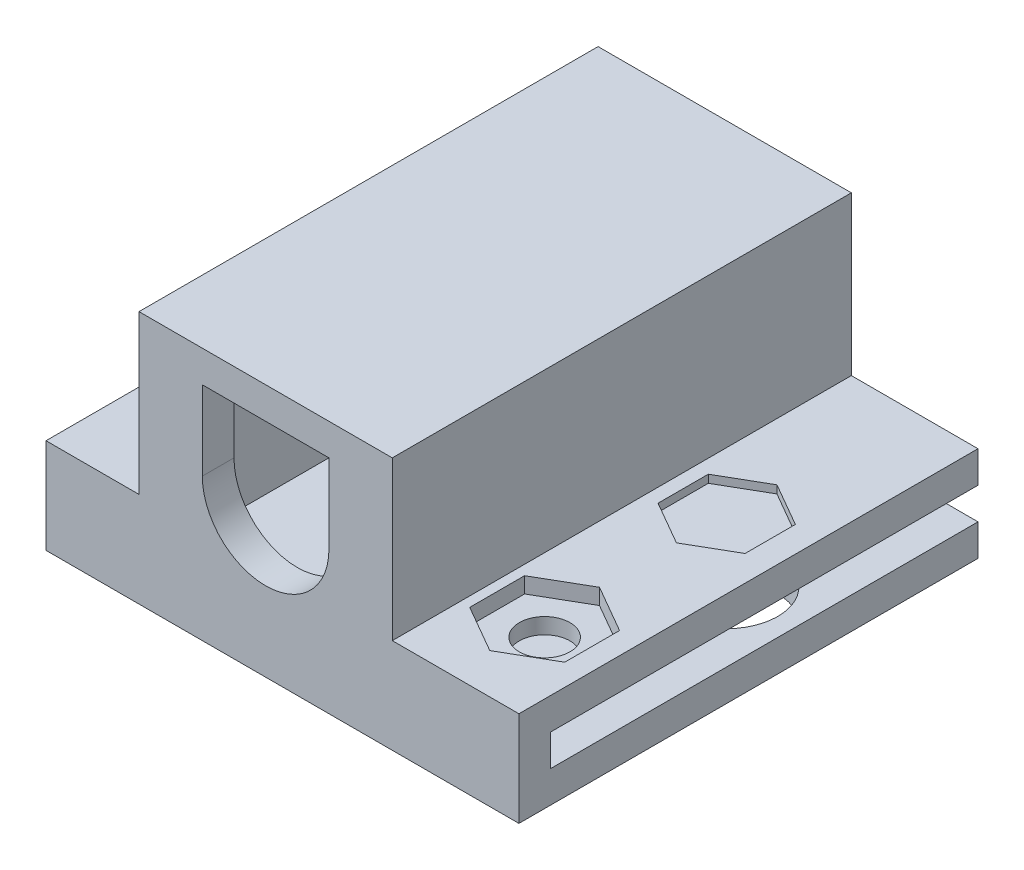
SolidWorks part; units mm, degrees
ref_plane "前视基准面" through (0, 0, 0) normal (0, 0, 1) x (1, 0, 0)
ref_plane "上视基准面" through (0, 0, 0) normal (0, 1, 0) x (1, 0, 0)
ref_plane "右视基准面" through (0, 0, 0) normal (1, 0, 0) x (0, 0, -1)
sketch "草图1" plane through (0, 0, 0) normal (0, 0, 1) x (1, 0, 0)
  line L1 (-13.875, -3) -> (-8, -3)
  line L2 (-13.875, -3) -> (-13.875, -9)
  line L3 (-13.875, -9) -> (16, -9)
  line L4 (5.5, 5) -> (-5.5, 5)
  line L5 (-6, 4.5) -> (-6, -4.5)
  line L6 (-5.5, -5) -> (5.5, -5)
  line L7 (6, -4.5) -> (6, 4.5)
  line L8 (5.5, 5) -> (-5.5, 5)
  line L9 (-6, 4.5) -> (-6, -4.5)
  line L10 (-5.5, -5) -> (5.5, -5)
  line L11 (6, -4.5) -> (6, 4.5)
  line L12 (-11.875, -7) -> (88.125, -7)
  line L13 (88.125, -7) -> (88.125, -5)
  line L14 (88.125, -5) -> (-11.875, -5)
  line L15 (-11.875, -5) -> (-11.875, -7)
  line L16 (-11.875, -7) -> (88.125, -7)
  line L17 (88.125, -7) -> (88.125, -5)
  line L18 (88.125, -5) -> (-11.875, -5)
  line L19 (-11.875, -5) -> (-11.875, -7)
  line L20 (16, -3) -> (16, -9)
  line L21 (-8, 7) -> (8, 7)
  line L22 (-8, 7) -> (-8, -3)
  line L23 (-8, -5) -> (8, -5)
  line L24 (8, 7) -> (8, -3)
  line L25 (8, -3) -> (16, -3)
  line L27 (0.8292, -1.25) -> (0.8292, 1.25)
  line L28 (0.8292, -1.25) -> (0.8292, 1.25)
  line L30 (-4, 0) -> (-4, 5)
  line L31 (-4, 5) -> (4, 5)
  line L32 (4, 0) -> (4, 5)
  arc A0 (-4, 0) -> (4, 0) centre (0, 0) ccw
  arc A1 (0.8292, 1.25) -> (0.8292, -1.25) centre (0, 0) ccw
  arc A2 (0.8292, 1.25) -> (0.8292, -1.25) centre (0, 0) ccw
  arc A4 (6, 4.5) -> (5.5, 5) centre (5.5, 4.5) ccw
  arc A5 (-5.5, 5) -> (-6, 4.5) centre (-5.5, 4.5) ccw
  arc A6 (-6, -4.5) -> (-5.5, -5) centre (-5.5, -4.5) ccw
  arc A7 (5.5, -5) -> (6, -4.5) centre (5.5, -4.5) ccw
  arc A8 (6, 4.5) -> (5.5, 5) centre (5.5, 4.5) ccw
  arc A9 (-5.5, 5) -> (-6, 4.5) centre (-5.5, 4.5) ccw
  arc A10 (-6, -4.5) -> (-5.5, -5) centre (-5.5, -4.5) ccw
  arc A11 (5.5, -5) -> (6, -4.5) centre (5.5, -4.5) ccw
  dimension "D11" = 8
  dimension "D3" = 2
  dimension "D4" = 2
  dimension "D5" = 2
  dimension "D6" = 2
  dimension "D7" = 2
  dimension "D8" = 8
  dimension "D9" = 2
  dimension "D1" = 0
  dimension "D2" = 0
  dimension "D10" = 0
extrude "凸台-拉伸1" add sketch "草图1" along normal blind 2 contours L10 A11 L11 A8 L8 L32 A0 L30 A9 L9 A10 | A11 L18 L20 L25 L24 L21 L22 L1 L2 L3 L16 L19 A10 L9 A9 L8 A8 L11 | L20 L18 L10 L19 L16
sketch "草图2" plane through (0, 0, 0) normal (0, 0, -1) x (-1, 0, 0)
  line L0 (-88.125, -5) -> (11.875, -5) construction
  line L1 (-6, 5) -> (6, 5)
  line L2 (-6, 5) -> (-6, -5)
  line L4 (-6, 4.5) -> (-6, -4.5)
  line L5 (-5.5, -5) -> (5.5, -5)
  line L6 (6, -4.5) -> (6, 4.5)
  line L7 (5.5, 5) -> (-5.5, 5)
  line L8 (-16, -3) -> (-16, -9)
  line L9 (-16, -9) -> (13.875, -9)
  line L10 (13.875, -9) -> (13.875, -3)
  line L11 (13.875, -3) -> (8, -3)
  line L12 (8, -3) -> (8, 7)
  line L13 (8, 7) -> (-8, 7)
  line L14 (-8, 7) -> (-8, -3)
  line L15 (-8, -3) -> (-16, -3)
  line L16 (-16, -3) -> (-16, -9)
  line L17 (-16, -9) -> (13.875, -9)
  line L18 (13.875, -9) -> (13.875, -3)
  line L19 (13.875, -3) -> (8, -3)
  line L20 (8, -3) -> (8, 7)
  line L21 (8, 7) -> (-8, 7)
  line L22 (-8, 7) -> (-8, -3)
  line L23 (-8, -3) -> (-16, -3)
  line L24 (-6, 4.5) -> (-6, -4.5)
  line L26 (6, -4.5) -> (6, 4.5)
  line L27 (5.5, 5) -> (-5.5, 5)
  line L28 (6, 5) -> (6, -5)
  line L33 (-6, -5) -> (-88.125, -5)
  line L37 (-88.125, -7) -> (11.875, -7)
  line L38 (-88.125, -5) -> (-88.125, -7)
  line L39 (11.875, -5) -> (-88.125, -5)
  line L40 (11.875, -7) -> (11.875, -5)
  line L41 (-88.125, -7) -> (11.875, -7)
  line L42 (-88.125, -5) -> (-88.125, -7)
  line L43 (11.875, -5) -> (6, -5)
  line L44 (11.875, -7) -> (11.875, -5)
  arc A4 (-5.5, 5) -> (-6, 4.5) centre (-5.5, 4.5) ccw
  arc A5 (-6, -4.5) -> (-5.5, -5) centre (-5.5, -4.5) ccw
  arc A6 (5.5, -5) -> (6, -4.5) centre (5.5, -4.5) ccw
  arc A7 (6, 4.5) -> (5.5, 5) centre (5.5, 4.5) ccw
  arc A8 (-5.5, 5) -> (-6, 4.5) centre (-5.5, 4.5) ccw
  arc A11 (6, 4.5) -> (5.5, 5) centre (5.5, 4.5) ccw
  point P26 (6, 0)
  line M20 (-16, -3) -> (-16, -9)
  line M21 (-16, -9) -> (13.875, -9)
  line M22 (13.875, -9) -> (13.875, -3)
  line M23 (13.875, -3) -> (8, -3)
  line M24 (8, -3) -> (8, 7)
  line M25 (8, 7) -> (-8, 7)
  line M26 (-8, 7) -> (-8, -3)
  line M27 (-8, -3) -> (-16, -3)
  line M28 (-4, 5) -> (4, 5)
  dimension "D3" = 0
  dimension "D4" = 0
  dimension "D5" = 0
  dimension "D1" = 0
  dimension "D2" = 0
extrude "凸台-拉伸2" add sketch "草图2" along normal offset from surface (27 mm away) 2 contours L44 L41 L16 L43 L2 L1 L28 L26 M21 M22 M23 M24 M25 M26 M27 M20 M28
sketch "草图4" plane through (0, -9, 0) normal (0, -1, 0) x (1, 0, 0)
  line L0 (9.33, -14.175) -> (13.92, -16.825) construction
  line L2 (11.625, -18.7274) -> (14.42, -17.1137)
  line L3 (14.42, -17.1137) -> (14.42, -13.8863)
  line L4 (-13.875, 2) -> (-13.875, -27)
  line L5 (-13.875, -27) -> (16, -27)
  line L6 (16, -27) -> (16, 2)
  line L7 (16, 2) -> (-13.875, 2)
  line L8 (-13.875, 2) -> (-13.875, -27)
  line L10 (16, -27) -> (16, 2)
  line L11 (16, 2) -> (-13.875, 2)
  line L12 (14.42, -13.8863) -> (11.625, -12.2726)
  line L13 (11.625, -12.2726) -> (8.83, -13.8863)
  line L14 (9.33, -14.175) -> (9.33, -16.825)
  line L15 (9.33, -16.825) -> (11.625, -18.15)
  line L16 (11.625, -18.15) -> (13.92, -16.825)
  line L17 (13.92, -16.825) -> (13.92, -14.175)
  line L18 (13.92, -14.175) -> (11.625, -12.85)
  line L19 (11.625, -12.85) -> (9.33, -14.175)
  line L20 (9.33, -14.175) -> (9.33, -16.825)
  line L21 (9.33, -16.825) -> (11.625, -18.15)
  line L22 (11.625, -18.15) -> (13.92, -16.825)
  line L23 (13.92, -16.825) -> (13.92, -14.175)
  line L24 (13.92, -14.175) -> (11.625, -12.85)
  line L25 (11.625, -12.85) -> (9.33, -14.175)
  line L26 (8.83, -13.8863) -> (8.83, -17.1137)
  line L27 (8.83, -17.1137) -> (11.625, -18.7274)
  line L31 (-13.875, -27) -> (16, -27)
  circle A0 centre (11.625, -15.5) radius 2.795 construction
  circle A1 centre (11.625, -15.5) radius 3.2274
  dimension "D3" = 0.5
  dimension "D1" = 0
  dimension "D2" = 0
extrude "切除-拉伸1" cut sketch "草图4" against normal blind 2 contours A1
sketch "草图5" plane through (0, -3, 0) normal (0, 1, 0) x (1, 0, 0)
  line L1 (11.625, 18.6754) -> (8.875, 17.0877)
  line L2 (8.875, 17.0877) -> (8.875, 13.9123)
  line L3 (8.875, 13.9123) -> (11.625, 12.3246)
  line L4 (16, -2) -> (16, 27)
  line L5 (16, 27) -> (8, 27)
  line L6 (8, 27) -> (8, -2)
  line L7 (8, -2) -> (16, -2)
  line L8 (16, -2) -> (16, 27)
  line L10 (8, 27) -> (8, -2)
  line L11 (8, -2) -> (16, -2)
  line L12 (11.625, 12.3246) -> (14.375, 13.9123)
  line L13 (14.375, 13.9123) -> (14.375, 17.0877)
  line L14 (14.375, 17.0877) -> (11.625, 18.6754)
  line L18 (16, 27) -> (8, 27)
  circle A0 centre (11.625, 15.5) radius 3
  circle A1 centre (11.625, 15.5) radius 1.25
  circle A2 centre (11.625, 15.5) radius 1.25
  circle A3 centre (11.625, 15.5) radius 2.75 construction
  dimension "D3" = 5.5
  dimension "D1" = 0
  dimension "D2" = 0
extrude "切除-拉伸2" cut sketch "草图5" against normal blind 0.5 contours L14 L1 L2 L3 L12 L13
sketch "草图6" plane through (0, -3, 0) normal (0, 1, 0) x (1, 0, 0)
  line L0 (11.625, 18.6754) -> (11.625, -2) construction
  line L2 (14.625, 2.2679) -> (14.625, 5.7321)
  line L3 (14.625, 5.7321) -> (11.625, 7.4641)
  line L4 (16, -2) -> (16, 27)
  line L5 (16, 27) -> (8, 27)
  line L6 (8, 27) -> (8, -2)
  line L7 (8, -2) -> (16, -2)
  line L8 (16, -2) -> (16, 27)
  line L10 (8, 27) -> (8, -2)
  line L11 (8, -2) -> (16, -2)
  line L12 (11.625, 7.4641) -> (8.625, 5.7321)
  line L13 (8.625, 5.7321) -> (8.625, 2.2679)
  line L14 (14.375, 13.9123) -> (14.375, 17.0877)
  line L15 (14.375, 17.0877) -> (11.625, 18.6754)
  line L16 (11.625, 18.6754) -> (8.875, 17.0877)
  line L17 (8.875, 17.0877) -> (8.875, 13.9123)
  line L18 (8.875, 13.9123) -> (11.625, 12.3246)
  line L19 (11.625, 12.3246) -> (14.375, 13.9123)
  line L20 (14.375, 13.9123) -> (14.375, 17.0877)
  line L21 (14.375, 17.0877) -> (11.625, 18.6754)
  line L22 (11.625, 18.6754) -> (8.875, 17.0877)
  line L23 (8.875, 17.0877) -> (8.875, 13.9123)
  line L24 (8.875, 13.9123) -> (11.625, 12.3246)
  line L25 (11.625, 12.3246) -> (14.375, 13.9123)
  line L26 (8.625, 2.2679) -> (11.625, 0.5359)
  line L27 (11.625, 0.5359) -> (14.625, 2.2679)
  line L31 (16, 27) -> (8, 27)
  circle A0 centre (11.625, 4) radius 3 construction
  dimension "D3" = 6
  dimension "D4" = 6
  dimension "D1" = 0
  dimension "D2" = 0
extrude "切除-拉伸3" cut sketch "草图6" against normal blind 1 contours L26 L27 L2 L3 L12 L13
sketch "草图7" plane through (0, -4, 0) normal (0, 1, 0) x (1, 0, 0)
  line L0 (11.625, 7.4641) -> (11.625, 0.5359) construction
  line L6 (8.625, 2.2679) -> (11.625, 0.5359)
  line L7 (11.625, 0.5359) -> (14.625, 2.2679)
  line L8 (14.625, 2.2679) -> (14.625, 5.7321)
  line L9 (14.625, 5.7321) -> (11.625, 7.4641)
  line L10 (11.625, 7.4641) -> (8.625, 5.7321)
  line L11 (8.625, 5.7321) -> (8.625, 2.2679)
  line L12 (8.625, 2.2679) -> (11.625, 0.5359)
  line L13 (11.625, 0.5359) -> (14.625, 2.2679)
  line L14 (14.625, 2.2679) -> (14.625, 5.7321)
  line L15 (14.625, 5.7321) -> (11.625, 7.4641)
  line L16 (11.625, 7.4641) -> (8.625, 5.7321)
  line L17 (8.625, 5.7321) -> (8.625, 2.2679)
  circle A0 centre (11.625, 4) radius 1.6
  dimension "D2" = 3.2
  dimension "D1" = 0
extrude "切除-拉伸4" cut sketch "草图7" against normal through all contours L0 A0 | A0 L0
sketch "草图8" plane through (0, 0, -27) normal (0, 0, -1) x (-1, 0, 0)
  line L0 (6, -5) -> (6, 5) construction
  line L1 (-6, 5) -> (6, 5)
  line L2 (-6, 5) -> (-6, 4)
  line L3 (-6, 4) -> (6, 4)
  line L4 (6, 5) -> (6, 4)
  dimension "D1" = 1
extrude "凸台-拉伸3" add sketch "草图8" against normal blind 1.6
